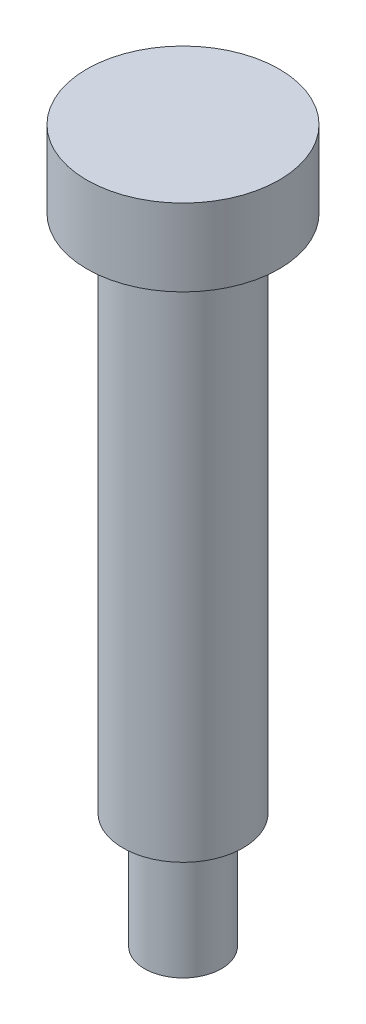
SolidWorks part; units mm, degrees
ref_plane "Front Plane" through (0, 0, 0) normal (0, 0, 1) x (1, 0, 0)
ref_plane "Top Plane" through (0, 0, 0) normal (0, 1, 0) x (1, 0, 0)
ref_plane "Right Plane" through (0, 0, 0) normal (1, 0, 0) x (0, 0, -1)
sketch "Sketch1" plane through (0, 0, 0) normal (0, 1, 0) x (1, 0, 0)
  circle A0 centre (0, 0) radius 5
  dimension "D1" = 10
extrude "Boss-Extrude1" add sketch "Sketch1" against normal blind 4
sketch "Sketch2" plane through (0, -4, 0) normal (0, -1, 0) x (1, 0, 0)
  circle A0 centre (0, 0) radius 3.125
  dimension "D1" = 6.25
extrude "Boss-Extrude2" add sketch "Sketch2" along normal blind 27
sketch "Sketch3" plane through (0, -31, 0) normal (0, -1, 0) x (1, 0, 0)
  circle A0 centre (0, 0) radius 2
  dimension "D1" = 4
extrude "Boss-Extrude3" add sketch "Sketch3" along normal blind 6
